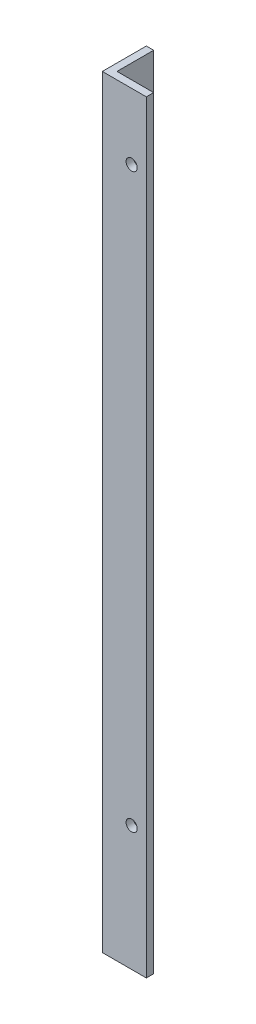
SolidWorks part; units mm, degrees
ref_plane "Front" through (0, 0, 0) normal (0, 0, 1) x (1, 0, 0)
ref_plane "Top" through (0, 0, 0) normal (0, 1, 0) x (1, 0, 0)
ref_plane "Right" through (0, 0, 0) normal (1, 0, 0) x (0, 0, -1)
sketch "Sketch1" plane through (0, 0, 0) normal (0, 1, 0) x (1, 0, 0)
  line L0 (3.175, 3.175) -> (3.175, 19.05)
  line L1 (0, 0) -> (19.05, 0)
  line L2 (0, 0) -> (0, 19.05)
  line L5 (3.175, 3.175) -> (19.05, 3.175)
  line L6 (0, 19.05) -> (3.175, 19.05)
  line L7 (19.05, 0) -> (19.05, 3.175)
  dimension "D1" = 19.05
  dimension "D2" = 3.175
extrude "Boss-Extrude1" add sketch "Sketch1" along normal blind 330.2
sketch "Sketch2" plane through (0, 0, -3.175) normal (0, 0, -1) x (-1, 0, 0)
  circle A0 centre (-12.7, 53.975) radius 2.413 construction
  circle A1 centre (-12.7, 53.975) radius 2.413
  circle A2 centre (-12.7, 301.625) radius 2.413 construction
  circle A3 centre (-12.7, 301.625) radius 2.413
extrude "Cut-Extrude1" cut sketch "Sketch2" against normal up to next
